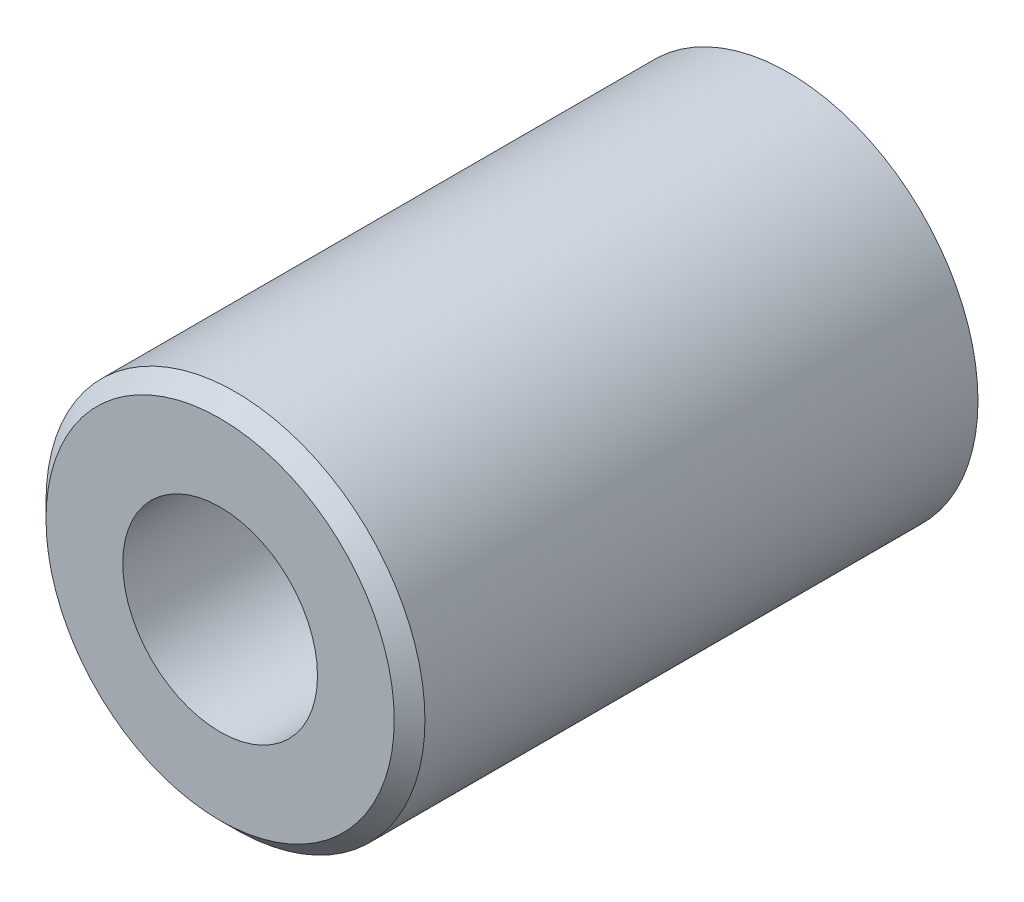
SolidWorks part; units mm, degrees
material "Plain Carbon Steel"
ref_plane "Front Plane" through (0, 0, 0) normal (0, 0, 1) x (1, 0, 0)
ref_plane "Top Plane" through (0, 0, 0) normal (0, 1, 0) x (1, 0, 0)
ref_plane "Right Plane" through (0, 0, 0) normal (1, 0, 0) x (0, 0, -1)
sketch "Sketch1" plane through (0, 0, 0) normal (0, 0, 1) x (1, 0, 0)
  line L0 (0, 3.2639) -> (0, 6.35) construction
  circle A0 centre (0, 0) radius 6.35
  circle A1 centre (0, 0) radius 3.2639
  dimension "OD" = 12.7
  dimension "ID" = 6.5278
  dimension "D1" = 3.0861
extrude "Extrude1" add sketch "Sketch1" along normal mid plane 19.05
chamfer "Chamfer1" distance 0.5144 angle 45 1 edges at (6.35, 0, 9.525)
sketch "Sketch6" plane through (0, 0, 9.525) normal (0, 0, -1) x (-1, 0, 0)
  line L0 (0, 0) -> (-3.2639, 0) construction
  line L1 (0, 0) -> (2.3079, 2.3079) construction
  circle A0 centre (0, 0) radius 3.2639 construction
  circle A3 centre (0, 0) radius 3.2639
  dimension "D1" = 135
equation "\"D1@Chamfer1\" = \"D1@Sketch1\"/6"
